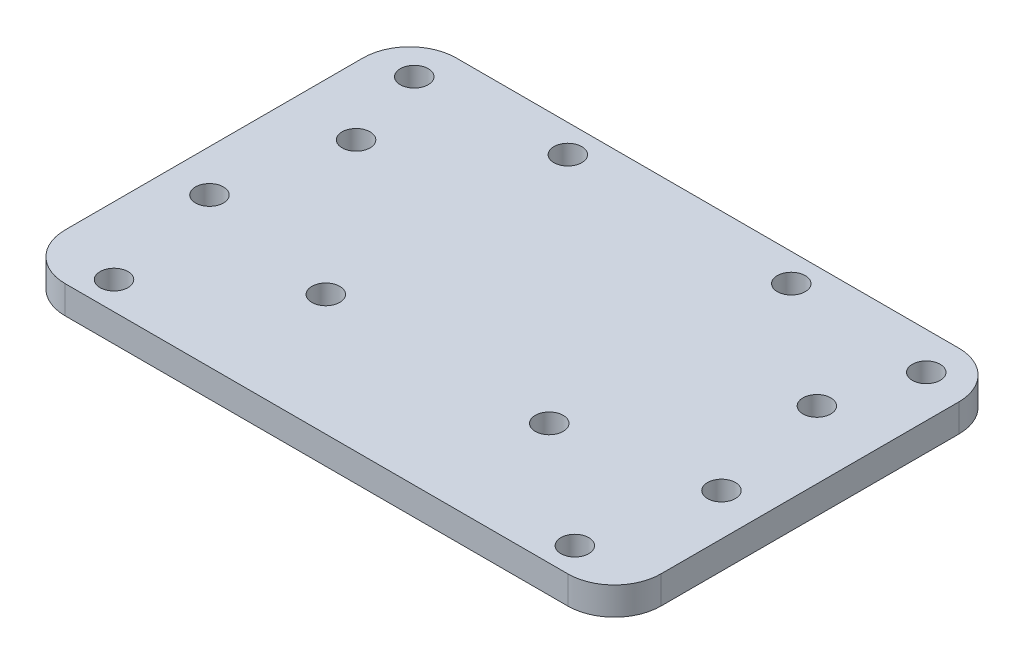
SolidWorks part; units mm, degrees
material "Thornel Mat VMA"
ref_plane "前视基准面" through (0, 0, 0) normal (0, 0, 1) x (1, 0, 0)
ref_plane "上视基准面" through (0, 0, 0) normal (0, 1, 0) x (1, 0, 0)
ref_plane "右视基准面" through (0, 0, 0) normal (1, 0, 0) x (0, 0, -1)
other "Configuration Table"
sketch "草图1" plane through (0, 0, 0) normal (0, 1, 0) x (1, 0, 0)
  line L0 (0, 0) -> (0, 22.5427) construction
  line L1 (-32, -16) -> (32, -16)
  line L2 (-32, -16) -> (-32, 16)
  line L3 (-32, 16) -> (32, 16)
  line L4 (32, -16) -> (32, 16)
  line L5 (-32, -16) -> (32, 16) construction
  line L6 (-32, 16) -> (32, -16) construction
  line L7 (0, 0) -> (42.2787, 0) construction
  line L8 (0, -10) -> (52.4839, -10) construction
  line L9 (-32, -16) -> (-32, -26)
  line L10 (-32, -26) -> (32, -26)
  line L11 (32, -26) -> (32, -16)
  circle A0 centre (27.5, 12) radius 1.5
  circle A3 centre (-27.5, 12) radius 1.5
  circle A4 centre (27.5, -10) radius 1.5
  circle A5 centre (24.75, 3) radius 1.5
  circle A7 centre (-27.5, -10) radius 1.5
  circle A9 centre (-24.75, 3) radius 1.5
  circle A10 centre (24.75, -23) radius 1.5
  circle A11 centre (-24.75, -23) radius 1.5
  circle A12 centre (12, 13) radius 1.5
  circle A13 centre (12, -13) radius 1.5
  circle A14 centre (-12, -13) radius 1.5
  circle A15 centre (-12, 13) radius 1.5
  point P0 (0, 0)
  dimension "D3" = 3
  dimension "D4" = 3
  dimension "D5" = 3
  dimension "D6" = 49.5
  dimension "D7" = 26
  dimension "D8" = 55
  dimension "D9" = 12
  dimension "D10" = 55
  dimension "D11" = 10
  dimension "D14" = 3
  dimension "D15" = 24
  dimension "D16" = 26
  dimension "D1" = 64
  dimension "D2" = 32
  dimension "D12" = 10
  dimension "D13" = 10
extrude "凸台-拉伸1" add sketch "草图1" along normal blind 3 contours A11 L1 A10 L4 L3 L2 A7 A5 A4 A0 A3 A9 | A11 L1 L9 L10 L11 A10
fillet "圆角2" radius 5 4 edges at (-32, 1.5, 26) (32, 1.5, 26) (32, 1.5, -16) (-32, 1.5, -16)
